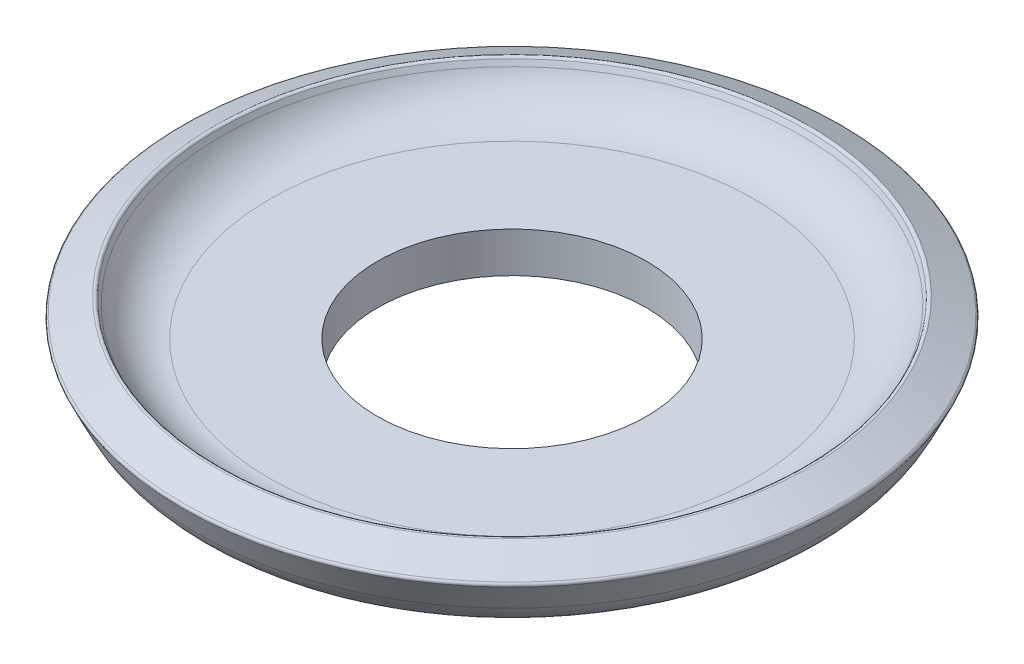
SolidWorks part; units mm, degrees
material "S235JR"
ref_plane "Front Plane" through (0, 0, 0) normal (0, 0, 1) x (1, 0, 0)
ref_plane "Top Plane" through (0, 0, 0) normal (0, 1, 0) x (1, 0, 0)
ref_plane "Right Plane" through (0, 0, 0) normal (1, 0, 0) x (0, 0, -1)
sketch "Sketch1" plane through (0, 0, 0) normal (0, 0, 1) x (1, 0, 0)
  line L0 (5, 1.1764) -> (9.9372, 1.1764)
  line L1 (11.7357, 2.3014) -> (12.2383, 3.3345)
  line L2 (12.1921, 3.4682) -> (11.0231, 4.037)
  line L3 (10.8895, 3.9908) -> (10.7973, 3.8014)
  line L4 (8.9989, 2.6764) -> (5, 2.6764)
  line L5 (0, 4.3712) -> (0, -2.8142) construction
  line L6 (5, 2.6764) -> (5, 1.1764)
  arc A0 (9.9372, 1.1764) -> (11.7357, 2.3014) centre (9.9372, 3.1764) ccw
  arc A1 (10.7973, 3.8014) -> (8.9989, 2.6764) centre (8.9989, 4.6764) cw
  arc A2 (12.1921, 3.4682) -> (12.2383, 3.3345) centre (12.1484, 3.3783) cw
  arc A3 (11.0231, 4.037) -> (10.8895, 3.9908) centre (10.9794, 3.947) ccw
  point P11 (11.1883, 1.1764)
  point P14 (10.25, 2.6764)
  point P17 (12.2821, 3.4245)
  point P20 (10.9332, 4.0807)
  dimension "D7" = 2
  dimension "D8" = 0.1
  dimension "D4" = 1.5
  dimension "D5" = 2.5
  dimension "D6" = 1.5
revolve "Revolve1" add sketch "Sketch1" angle 360 about L5
